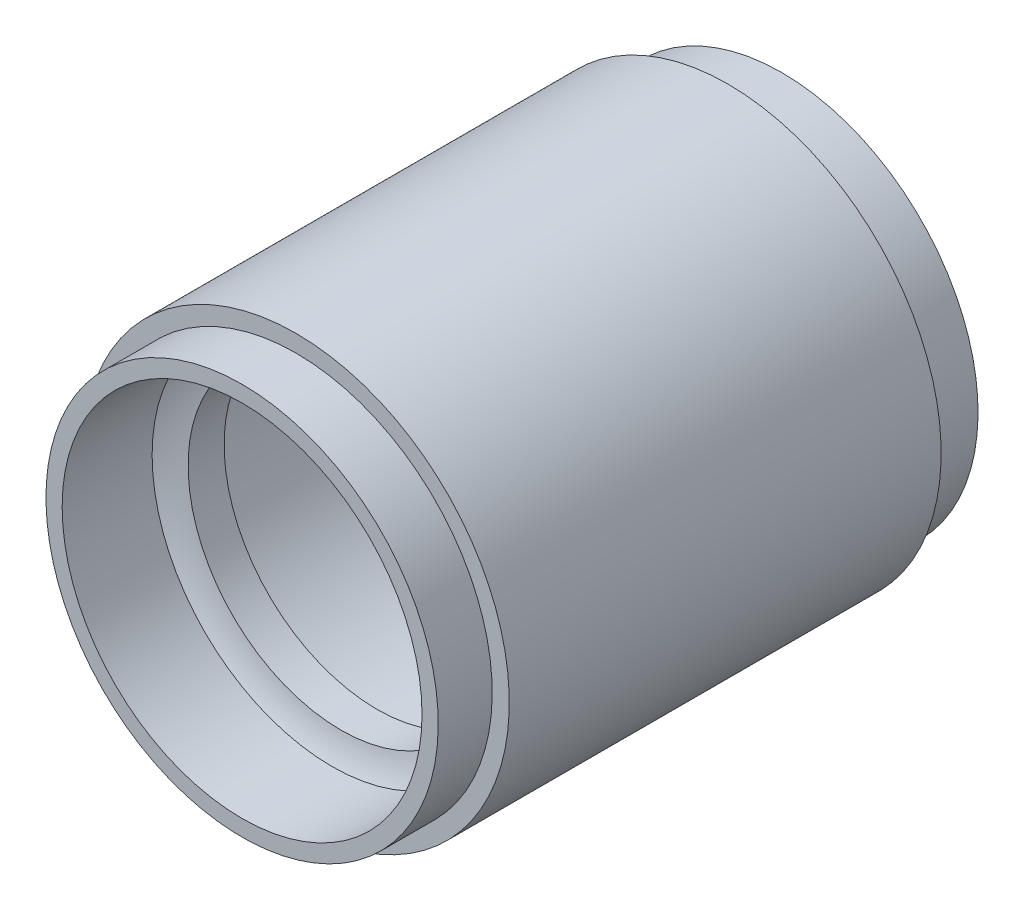
SolidWorks part; units mm, degrees
ref_plane "정면" through (0, 0, 0) normal (0, 0, 1) x (1, 0, 0)
ref_plane "윗면" through (0, 0, 0) normal (0, 1, 0) x (1, 0, 0)
ref_plane "우측면" through (0, 0, 0) normal (1, 0, 0) x (0, 0, -1)
sketch "스케치1" plane through (0, 0, 0) normal (1, 0, 0) x (0, 0, -1)
  line L0 (0, 0) -> (0, 11.85) construction
  line L1 (0, 0) -> (-15, 0) construction
  line L2 (12, 11.85) -> (-12, 11.85)
  line L3 (-12, 11.85) -> (-12, 10.9)
  line L4 (-12, 10.9) -> (-15, 10.9)
  line L5 (-15, 10.9) -> (-15, 10)
  line L6 (-15, 10) -> (-10, 10)
  line L7 (-15, 10) -> (-15, 0) construction
  line L8 (-9.5, 8.5) -> (-7.5, 8.5)
  line L9 (-7.5, 8.5) -> (-6.8174, 10.7324)
  line L10 (-6.8174, 10.7324) -> (6.8174, 10.7324)
  line L11 (7.5, 8.5) -> (6.8174, 10.7324)
  line L12 (9.5, 8.5) -> (7.5, 8.5)
  line L13 (15, 10) -> (10, 10)
  line L14 (15, 10.9) -> (15, 10)
  line L15 (12, 10.9) -> (15, 10.9)
  line L16 (12, 11.85) -> (12, 10.9)
  arc A0 (-10, 10) -> (-9.5, 8.5) centre (-14.2865, 7.7378) cw
  arc A1 (10, 10) -> (9.5, 8.5) centre (14.2865, 7.7378) ccw
  point P18 (0, 10.7324)
  dimension "D1" = 20
  dimension "D2" = 1.5
  dimension "D3" = 0.5
  dimension "D4" = 20
  dimension "D5" = 2
  dimension "D6" = 23.7
  dimension "D7" = 21.8
  dimension "D8" = 3
  dimension "D9" = 30
revolve "회전1" add sketch "스케치1" angle 360 about L1
